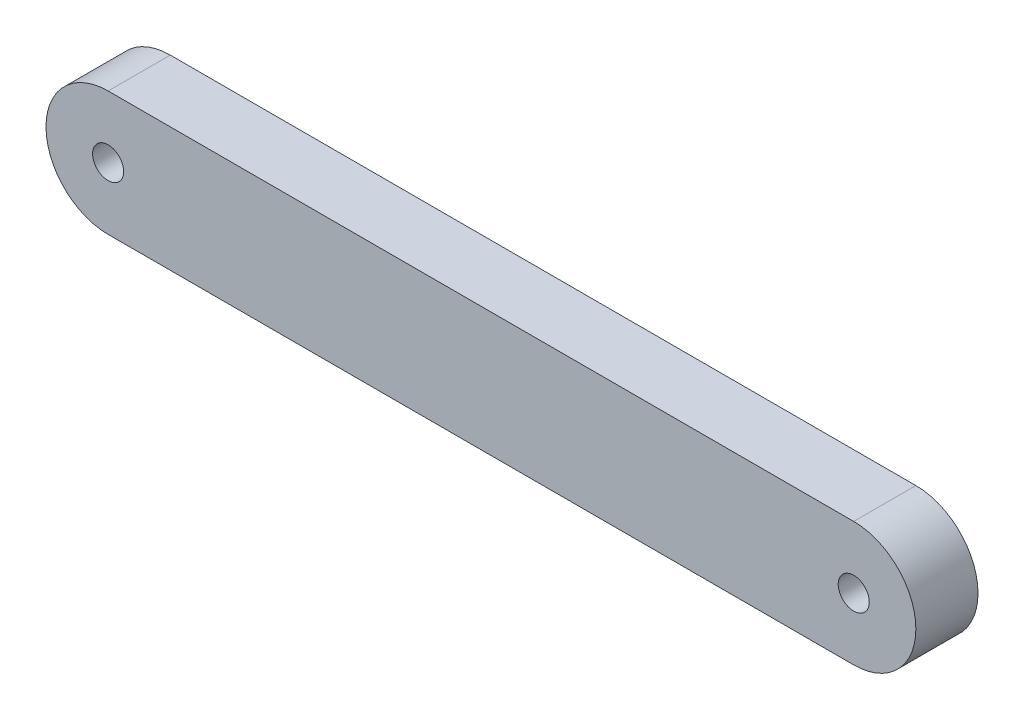
SolidWorks part; units mm, degrees
ref_plane "Front Plane" through (0, 0, 0) normal (0, 0, 1) x (1, 0, 0)
ref_plane "Top Plane" through (0, 0, 0) normal (0, 1, 0) x (1, 0, 0)
ref_plane "Right Plane" through (0, 0, 0) normal (1, 0, 0) x (0, 0, -1)
sketch "Sketch1" plane through (0, 0, 0) normal (0, 0, 1) x (1, 0, 0)
  line L1 (0, 6.35) -> (76.2, 6.35)
  line L2 (0, -6.35) -> (76.2, -6.35)
  circle A0 centre (0, 0) radius 6.35
  circle A1 centre (76.2, 0) radius 6.35
  circle A2 centre (0, 0) radius 1.5875
  circle A3 centre (76.2, 0) radius 1.5875
  dimension "D2" = 12.7
  dimension "D3" = 3.175
  dimension "D1" = 76.2
extrude "Boss-Extrude1" add sketch "Sketch1" along normal blind 6.35 contours A1 L1 A0 L2 | A0 A2 | A1 A3
